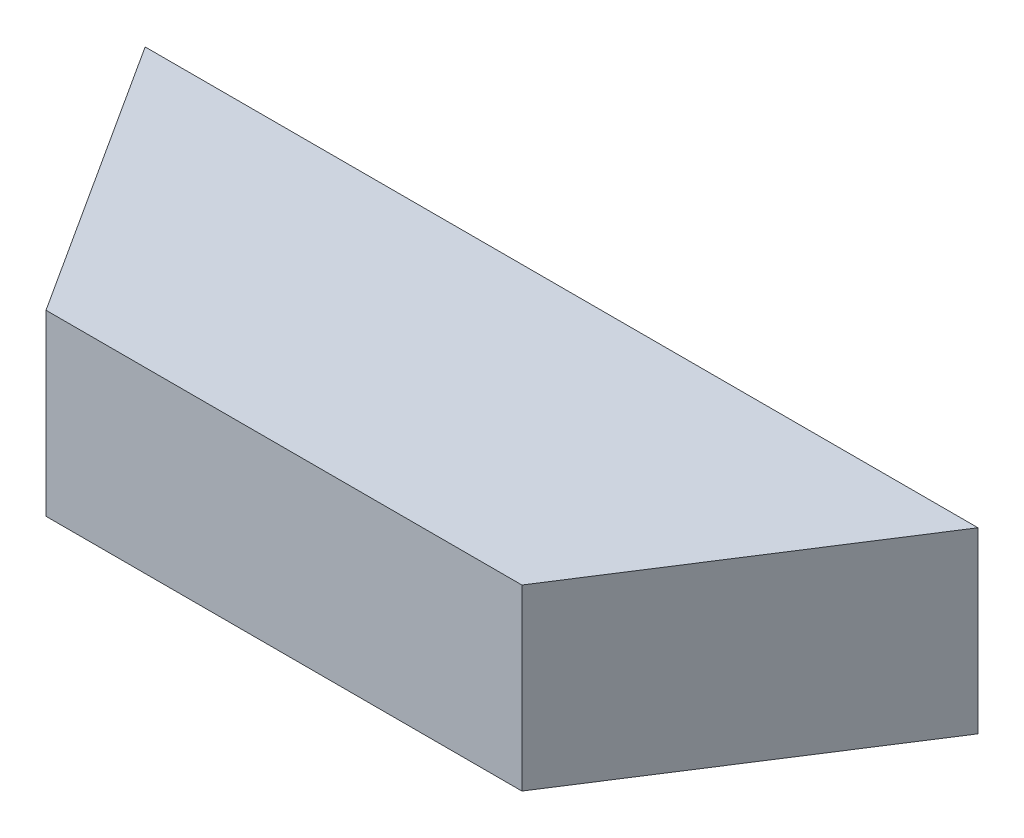
SolidWorks part; units mm, degrees
ref_plane "Front Plane" through (0, 0, 0) normal (0, 0, 1) x (1, 0, 0)
ref_plane "Top Plane" through (0, 0, 0) normal (0, 1, 0) x (1, 0, 0)
ref_plane "Right Plane" through (0, 0, 0) normal (1, 0, 0) x (0, 0, -1)
sketch "Sketch1" plane through (0, 0, 0) normal (0, 1, 0) x (1, 0, 0)
  line L0 (0, 0) -> (-152.4, 0)
  line L1 (-152.4, 0) -> (-209.55, 88.9)
  line L2 (-209.55, 88.9) -> (57.15, 88.9)
  line L3 (57.15, 88.9) -> (0, 0)
  point P3 (-76.2, 88.9)
  dimension "D1" = 152.4
  dimension "D2" = 266.7
  dimension "D3" = 88.9
  dimension "D4" = 76.2
extrude "Boss-Extrude1" add sketch "Sketch1" along normal blind 57.15
shell "Shell1" thickness 1.5875
